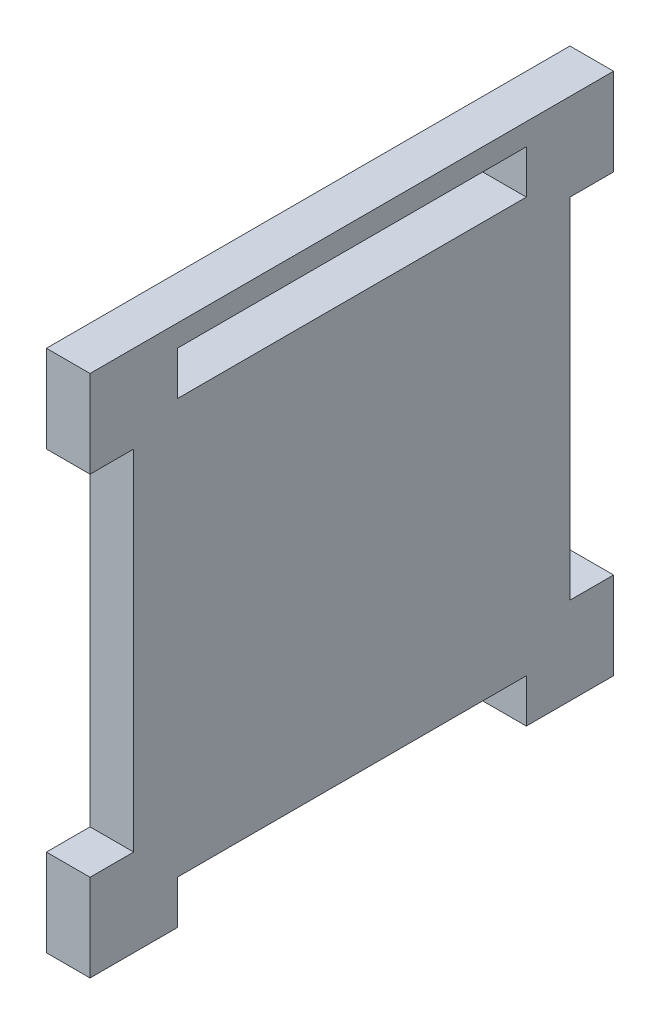
SolidWorks part; units mm, degrees
ref_plane "Front Plane" through (0, 0, 0) normal (0, 0, 1) x (1, 0, 0)
ref_plane "Top Plane" through (0, 0, 0) normal (0, 1, 0) x (1, 0, 0)
ref_plane "Right Plane" through (0, 0, 0) normal (1, 0, 0) x (0, 0, -1)
sketch "Sketch1" plane through (0, 0, 0) normal (0, 0, 1) x (1, 0, 0)
  line L0 (107.95, 38.1) -> (0, 38.1) construction
  line L1 (114.3, -38.1) -> (107.95, -38.1)
  line L2 (114.3, -38.1) -> (114.3, 38.1)
  line L3 (114.3, 38.1) -> (107.95, 38.1)
  line L4 (107.95, -38.1) -> (107.95, 38.1)
  dimension "D1" = 6.35
extrude "Boss-Extrude1" add sketch "Sketch1" along normal blind 63.5
sketch "Sketch2" plane through (114.3, 0, 0) normal (1, 0, 0) x (0, 0, -1)
  line L0 (-63.5, -38.1) -> (-63.5, 38.1) construction
  line L1 (-69.85, -38.1) -> (-63.5, -38.1)
  line L2 (-69.85, -38.1) -> (-69.85, -25.4)
  line L3 (-69.85, -25.4) -> (-63.5, -25.4)
  line L4 (-63.5, -38.1) -> (-63.5, -25.4)
  line L5 (-63.5, -25.4) -> (-69.85, -25.4) construction
  line L6 (-63.5, 25.4) -> (-69.85, 25.4) construction
  line L7 (-63.5, 25.4) -> (-69.85, 25.4)
  line L8 (-63.5, 25.4) -> (-63.5, 38.1)
  line L9 (-63.5, 38.1) -> (-69.85, 38.1)
  line L10 (-69.85, 25.4) -> (-69.85, 38.1)
  line L11 (-31.75, -38.1) -> (-31.75, 38.1) construction
  line L12 (-63.5, -38.1) -> (0, -38.1) construction
  line L13 (-63.5, 38.1) -> (0, 38.1) construction
  line L14 (6.35, 25.4) -> (6.35, 38.1)
  line L15 (0, 38.1) -> (6.35, 38.1)
  line L16 (0, 25.4) -> (0, 38.1)
  line L17 (0, 25.4) -> (6.35, 25.4)
  line L18 (0, -38.1) -> (0, -25.4)
  line L19 (6.35, -25.4) -> (0, -25.4)
  line L20 (6.35, -38.1) -> (6.35, -25.4)
  line L21 (6.35, -38.1) -> (0, -38.1)
  dimension "D1" = 6.35
  dimension "D2" = 12.7
extrude "Boss-Extrude2" add sketch "Sketch2" against normal blind 6.35
sketch "Sketch3" plane through (114.3, 0, 0) normal (1, 0, 0) x (0, 0, -1)
  line L4 (-6.35, 34.925) -> (-57.15, 34.925)
  line L5 (-57.15, 34.925) -> (-57.15, 28.575)
  line L6 (-57.15, 28.575) -> (-6.35, 28.575)
  line L7 (-6.35, 28.575) -> (-6.35, 34.925)
  line L8 (-6.35, 34.925) -> (-57.15, 34.925)
  line L9 (-57.15, 34.925) -> (-57.15, 28.575)
  line L10 (-57.15, 28.575) -> (-6.35, 28.575)
  line L11 (-6.35, 28.575) -> (-6.35, 34.925)
  line L24 (-69.85, -38.1) -> (6.35, -38.1) construction
  line L25 (-6.35, -31.75) -> (-57.15, -31.75)
  line L26 (-6.35, -31.75) -> (-6.35, -38.1)
  line L27 (-6.35, -38.1) -> (-57.15, -38.1)
  line L28 (-57.15, -31.75) -> (-57.15, -38.1)
  dimension "D1" = 0
extrude "Cut-Extrude1" cut sketch "Sketch3" against normal through all
